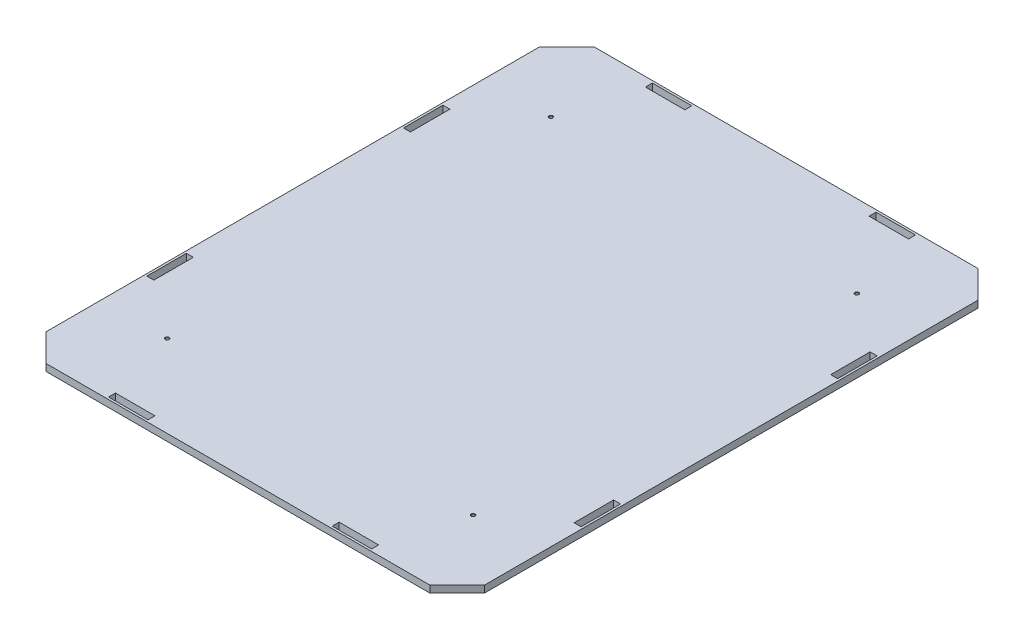
SolidWorks part; units mm, degrees
ref_plane "Front Plane" through (0, 0, 0) normal (0, 0, 1) x (1, 0, 0)
ref_plane "Top Plane" through (0, 0, 0) normal (0, 1, 0) x (1, 0, 0)
ref_plane "Right Plane" through (0, 0, 0) normal (1, 0, 0) x (0, 0, -1)
sketch "Sketch2" plane through (0, 0, 0) normal (0, 1, 0) x (1, 0, 0)
  line L1 (-200, -250) -> (200, -250)
  line L2 (-200, -250) -> (-200, 250)
  line L3 (-200, 250) -> (200, 250)
  line L4 (200, -250) -> (200, 250)
  line L5 (-200, -250) -> (200, 250) construction
  line L6 (-200, 250) -> (200, -250) construction
  point P0 (0, 0)
  dimension "D1" = 400
  dimension "D2" = 500
extrude "Boss-Extrude2" add sketch "Sketch2" along normal blind 6.35
sketch "Sketch3" plane through (0, 6.35, 0) normal (0, 1, 0) x (1, 0, 0)
  line L0 (-139.5, 250) -> (-139.5, -250) construction
  line L1 (200, 250) -> (-200, 250) construction
  line L2 (-200, -250) -> (200, -250) construction
  line L3 (-200, 175) -> (200, 175) construction
  line L4 (-200, 250) -> (-200, -250) construction
  line L5 (200, -250) -> (200, 250) construction
  line L6 (-200, 0) -> (200, 0) construction
  line L7 (0, 250) -> (0, -250) construction
  line L8 (139.5, 250) -> (139.5, -250) construction
  line L9 (-200, -175) -> (200, -175) construction
  circle A0 centre (-139.5, 175) radius 7.6335
  circle A2 centre (139.5, -175) radius 3.266
  circle A4 centre (139.5, 175) radius 10.436
  circle A5 centre (-139.5, -175) radius 13.4263
  point P28 (0, 0)
  dimension "D1" = 139.5
  dimension "D2" = 175
hole_wizard "M3.5x0.6 Tapped Hole2" positions "Sketch6" profile "Sketch7" tap size "M3.5x0.6" standard "ANSI Metric" end condition through all
sketch "Sketch6" plane through (0, 6.35, 0) normal (0, 1, 0) x (1, 0, 0)
  point P0 (-139.5, 175)
  point P3 (139.5, 175)
  point P6 (-139.5, -175)
  point P9 (139.5, -175)
sketch "Sketch7" plane through (-139.5, 6.35, -175) normal (1, 0, 0) x (0, 0, 1)
  line L0 (0, 0) -> (0, 6.35)
  line L1 (0, 6.35) -> (1.45, 6.35)
  line L2 (1.45, 6.35) -> (1.45, 0.325)
  line L3 (1.45, 0.325) -> (1.775, 0)
  line L5 (1.775, 0) -> (0, 0)
  line L6 (-1.45, 0.325) -> (-1.775, 0) construction
  line L11 (0, -6.35) -> (0, 107.95) construction
  dimension "Thread Major Dia." = 2.9
  dimension "Thru Tap Drill Depth" = 6.35
  dimension "Near C'Sink Dia." = 3.55
  dimension "Near C'Sink Angle" = 90
chamfer "Chamfer1" distance 25 angle 45 4 edges at (-200, 3.175, -250) (200, 3.175, -250) (-200, 3.175, 250) (200, 3.175, 250)
sketch "Sketch9" plane through (0, 6.35, 0) normal (0, 1, 0) x (1, 0, 0)
  line L0 (-187.5, -248) -> (198, -248) construction
  line L1 (198, 135) -> (191.65, 135)
  line L2 (191.65, 99) -> (191.65, 135)
  line L3 (198, -248) -> (198, 223.0086) construction
  line L4 (198, 99) -> (191.65, 99)
  line L5 (-175, -250) -> (175, -250) construction
  line L6 (-120, -250) -> (-120, -216.1128) construction
  line L7 (0, -250) -> (0, -204.2707) construction
  line L8 (0, 250) -> (0, -250) construction
  line L9 (120, -241.65) -> (84, -241.65)
  line L10 (-120, -248) -> (-84, -248)
  line L11 (-120, -248) -> (-120, -241.65)
  line L12 (-120, -241.65) -> (-84, -241.65)
  line L13 (-84, -248) -> (-84, -241.65)
  line L14 (84, -248) -> (84, -241.65)
  line L15 (120, -248) -> (84, -248)
  line L16 (120, -248) -> (120, -241.65)
  line L17 (-200, 0) -> (200, 0) construction
  line L18 (-120, 241.65) -> (-84, 241.65)
  line L19 (-84, 248) -> (-84, 241.65)
  line L20 (-120, 248) -> (-84, 248)
  line L21 (-120, 248) -> (-120, 241.65)
  line L22 (120, 248) -> (120, 241.65)
  line L23 (120, 248) -> (84, 248)
  line L24 (84, 248) -> (84, 241.65)
  line L25 (120, 241.65) -> (84, 241.65)
  line L26 (200, -135) -> (111.3102, -135) construction
  line L27 (200, -225) -> (200, 225) construction
  line L28 (198, 99) -> (198, 135)
  line L29 (198, -99) -> (191.65, -99)
  line L30 (198, -99) -> (198, -135)
  line L31 (198, -135) -> (191.65, -135)
  line L32 (191.65, -99) -> (191.65, -135)
  line L33 (0, 250) -> (0, -250) construction
  line L34 (-198, -135) -> (-191.65, -135)
  line L35 (-191.65, -99) -> (-191.65, -135)
  line L36 (-198, -99) -> (-191.65, -99)
  line L37 (-198, -99) -> (-198, -135)
  line L38 (-198, 99) -> (-198, 135)
  line L39 (-198, 99) -> (-191.65, 99)
  line L40 (-191.65, 99) -> (-191.65, 135)
  line L41 (-198, 135) -> (-191.65, 135)
  dimension "D1" = 2
  dimension "D2" = 120
  dimension "D3" = 6.35
  dimension "D4" = 36
  dimension "D5" = 135
  dimension "D6" = 6.35
  dimension "D7" = 36
  dimension "D8" = 2
extrude "Cut-Extrude1" cut sketch "Sketch9" against normal through all
